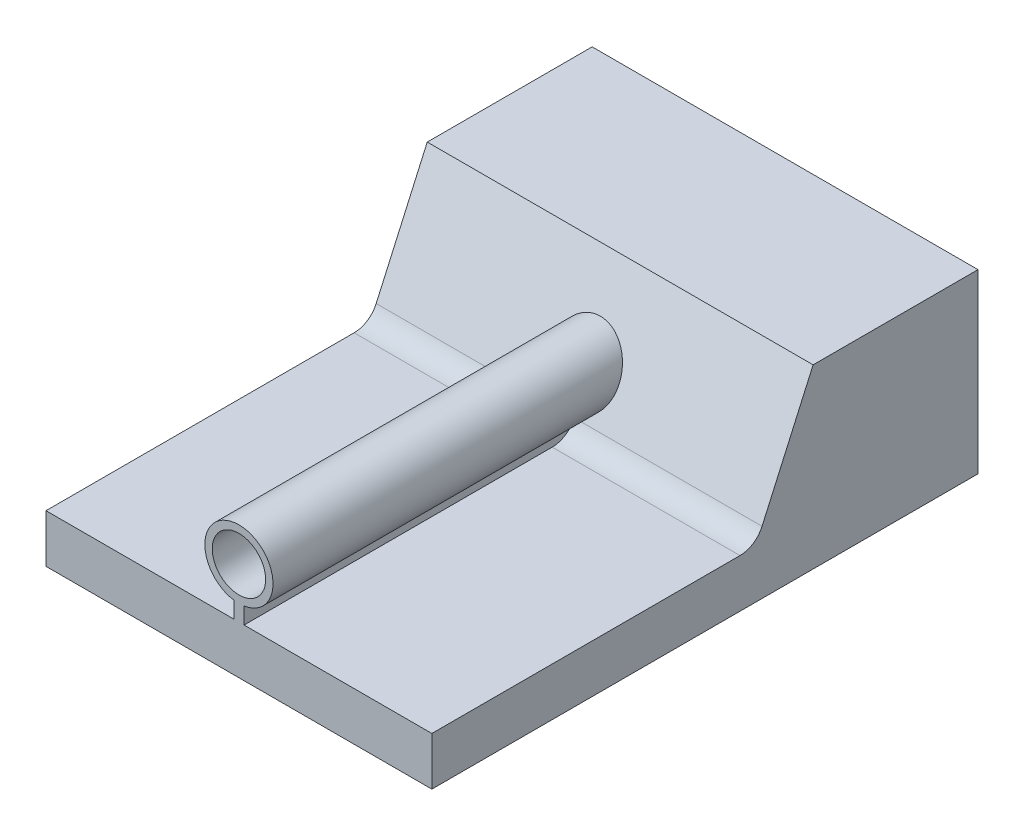
SolidWorks part; units mm, degrees
ref_plane "Front Plane" through (0, 0, 0) normal (0, 0, 1) x (1, 0, 0)
ref_plane "Top Plane" through (0, 0, 0) normal (0, 1, 0) x (1, 0, 0)
ref_plane "Right Plane" through (0, 0, 0) normal (1, 0, 0) x (0, 0, -1)
sketch "Sketch16" plane through (0, 0, 0) normal (1, 0, 0) x (0, 0, -1)
  line L0 (0, 0) -> (107.8519, 0)
  line L1 (107.8519, 0) -> (107.8519, 34.925)
  line L2 (107.8519, 34.925) -> (75.2877, 34.925)
  line L3 (75.2877, 34.925) -> (63.9428, 9.525)
  line L4 (63.9428, 9.525) -> (0, 9.525)
  line L5 (0, 9.525) -> (0, 0)
  dimension "D1" = 34.925
  dimension "D2" = 9.525
extrude "Extrude7" add sketch "Sketch16" along normal blind 76.2
ref_plane "Plane4" through (0, 0, 0) normal (0, 0, 1) x (1, 0, 0)
sketch "Sketch17" plane through (0, 0, 0) normal (0, 0, 1) x (1, 0, 0)
  line L0 (39.116, 9.525) -> (37.084, 9.525)
  line L3 (39.116, 9.525) -> (39.116, 12.7)
  line L4 (39.116, 12.7) -> (39.116, 12.7771)
  line L5 (37.084, 9.525) -> (37.084, 12.7)
  line L6 (37.084, 12.7) -> (37.084, 12.7771)
  arc A0 (39.116, 12.7771) -> (37.084, 12.7771) centre (38.1, 19.4313) ccw
  circle A1 centre (38.1, 19.4313) radius 5.2688
  point P1 (38.1, 12.7)
  point P5 (38.1, 26.1625)
  point P10 (39.116, 26.1625)
  point P13 (37.084, 26.1625)
extrude "Extrude8" add sketch "Sketch17" against normal up to body
fillet "Fillet1" radius 4.7752 2 edges at (18.542, 9.525, -63.9428) (57.658, 9.525, -63.9428)
